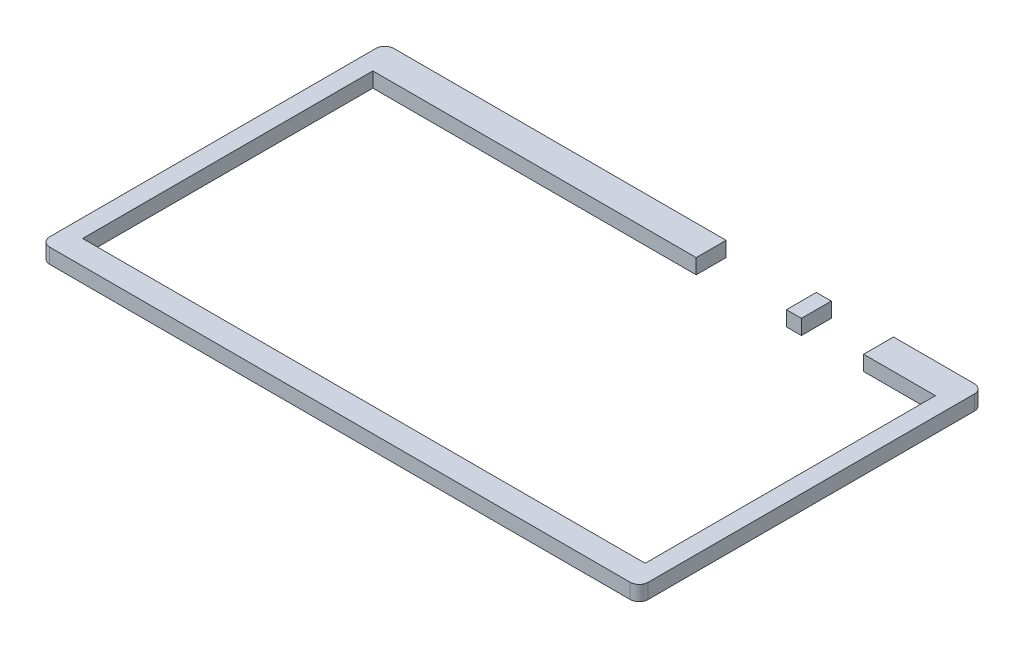
SolidWorks part; units mm, degrees
ref_plane "Front Plane" through (0, 0, 0) normal (0, 0, 1) x (1, 0, 0)
ref_plane "Top Plane" through (0, 0, 0) normal (0, 1, 0) x (1, 0, 0)
ref_plane "Right Plane" through (0, 0, 0) normal (1, 0, 0) x (0, 0, -1)
sketch "Sketch1" plane through (0, 0, 0) normal (0, 1, 0) x (1, 0, 0)
  line L0 (183.15, 133.35) -> (189.5, 133.35)
  line L1 (3.81, 0) -> (250.19, 0)
  line L2 (0, 3.81) -> (0, 142.24)
  line L3 (3.81, 146.05) -> (144.85, 146.05)
  line L4 (254, 3.81) -> (254, 142.24)
  line L5 (7.62, 133.35) -> (144.85, 133.35)
  line L6 (7.62, 133.35) -> (7.62, 10.16)
  line L7 (7.62, 10.16) -> (246.38, 10.16)
  line L8 (246.38, 133.35) -> (246.38, 10.16)
  line L10 (215.9, 146.05) -> (215.9, 133.35)
  line L12 (189.5, 146.05) -> (189.5, 133.35)
  line L14 (183.15, 146.05) -> (183.15, 133.35)
  line L16 (144.85, 146.05) -> (144.85, 133.35)
  line L17 (215.9, 133.35) -> (246.38, 133.35)
  line L18 (183.15, 146.05) -> (189.5, 146.05)
  line L19 (215.9, 146.05) -> (250.19, 146.05)
  arc A0 (250.19, 0) -> (254, 3.81) centre (250.19, 3.81) ccw
  arc A1 (250.19, 146.05) -> (254, 142.24) centre (250.19, 142.24) cw
  arc A2 (0, 142.24) -> (3.81, 146.05) centre (3.81, 142.24) cw
  arc A3 (3.81, 0) -> (0, 3.81) centre (3.81, 3.81) cw
  point P11 (254, 0)
  point P14 (254, 146.05)
  point P17 (0, 146.05)
  point P20 (0, 0)
  dimension "D7" = 3.81
  dimension "D1" = 254
  dimension "D2" = 146.05
  dimension "D3" = 7.62
  dimension "D4" = 12.7
  dimension "D5" = 10.16
  dimension "D6" = 7.62
  dimension "D8" = 38.3
  dimension "D9" = 26.4
  dimension "D10" = 38.1
  dimension "D11" = 6.35
extrude "Boss-Extrude1" add sketch "Sketch1" along normal blind 6.35
sketch "Sketch2" plane through (0, 6.35, 0) normal (0, 1, 0) x (1, 0, 0)
  circle A0 centre (167.1, 17.35) radius 1.35
  circle A1 centre (167.1, 66.35) radius 1.35
  circle A2 centre (225.1, 17.35) radius 1.35
  circle A3 centre (225.1, 66.35) radius 1.35
  dimension "D1" = 2.7
  dimension "D2" = 2.7
  dimension "D3" = 2.7
  dimension "D4" = 2.7
